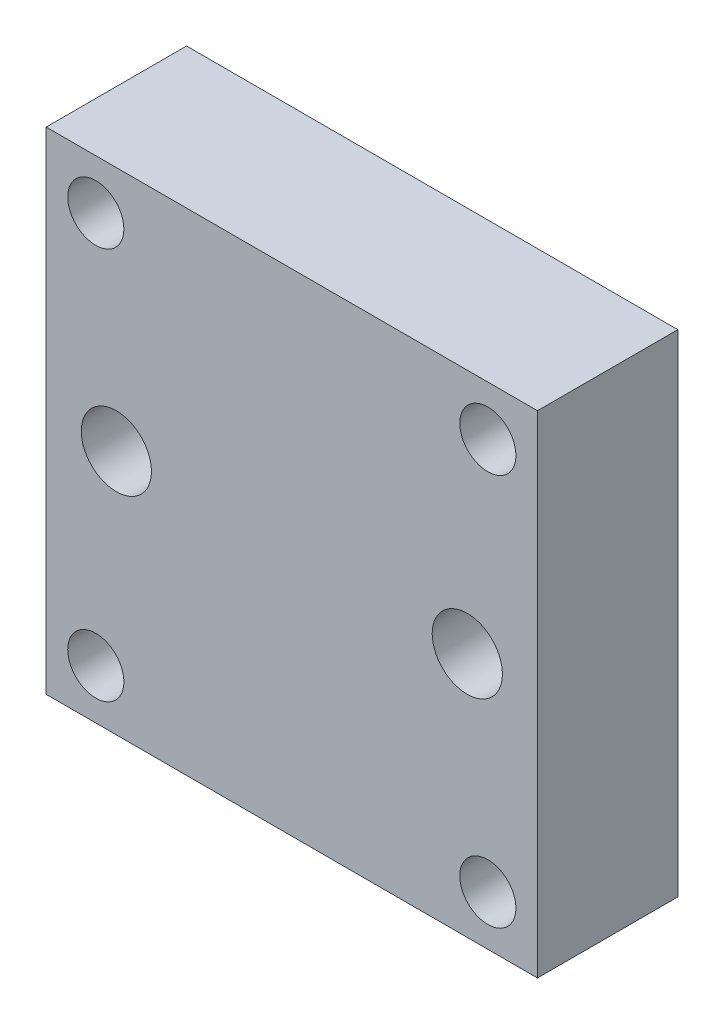
SolidWorks part; units mm, degrees
ref_plane "Front Plane" through (0, 0, 0) normal (0, 0, 1) x (1, 0, 0)
ref_plane "Top Plane" through (0, 0, 0) normal (0, 1, 0) x (1, 0, 0)
ref_plane "Right Plane" through (0, 0, 0) normal (1, 0, 0) x (0, 0, -1)
sketch "Sketch1" plane through (0, 0, 0) normal (0, 0, 1) x (1, 0, 0)
  line L0 (-14.7222, 2.4703) -> (20.2778, 2.4703) construction
  line L1 (-14.7222, 19.9703) -> (20.2778, 19.9703)
  line L2 (-14.7222, 19.9703) -> (-14.7222, -15.0297)
  line L3 (-14.7222, -15.0297) -> (20.2778, -15.0297)
  line L4 (20.2778, 19.9703) -> (20.2778, -15.0297)
  line L5 (-14.7222, 19.9703) -> (20.2778, -15.0297) construction
  line L6 (20.2778, 19.9703) -> (-14.7222, -15.0297) construction
  line L7 (2.7778, 19.9703) -> (2.7778, -15.0297) construction
  circle A1 centre (16.7422, -11.4942) radius 2
  circle A2 centre (16.7422, 16.4347) radius 2
  circle A3 centre (-11.1867, 16.4347) radius 2
  circle A4 centre (-11.1867, -11.4942) radius 2
  circle A5 centre (15.2778, 2.4703) radius 2.5
  circle A6 centre (-9.7222, 2.4703) radius 2.5
  point P4 (2.7778, 2.5926)
  dimension "D4" = 4
  dimension "D6" = 5
  dimension "D1" = 35
  dimension "D2" = 35
  dimension "D5" = 5
extrude "Boss-Extrude1" add sketch "Sketch1" along normal blind 10
